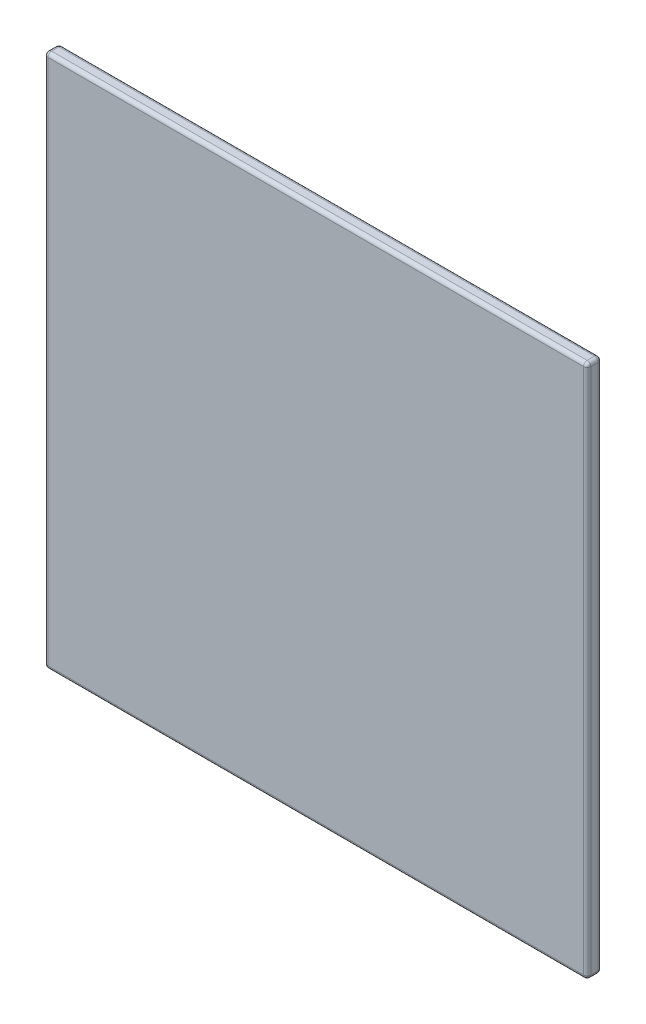
SolidWorks part; units mm, degrees
ref_plane "Front Plane" through (0, 0, 0) normal (0, 0, 1) x (1, 0, 0)
ref_plane "Top Plane" through (0, 0, 0) normal (0, 1, 0) x (1, 0, 0)
ref_plane "Right Plane" through (0, 0, 0) normal (1, 0, 0) x (0, 0, -1)
sketch "Sketch1" plane through (0, 0, 0) normal (0, 0, 1) x (1, 0, 0)
  line L1 (-37.35, -36.75) -> (37.35, -36.75)
  line L2 (-37.35, -36.75) -> (-37.35, 36.75)
  line L3 (-37.35, 36.75) -> (37.35, 36.75)
  line L4 (37.35, -36.75) -> (37.35, 36.75)
  line L5 (-37.35, -36.75) -> (37.35, 36.75) construction
  line L6 (-37.35, 36.75) -> (37.35, -36.75) construction
  point P0 (0, 0)
  dimension "D1" = 74.7
  dimension "D2" = 73.5
extrude "Boss-Extrude1" add sketch "Sketch1" along normal blind 2
fillet "Fillet1" radius 0.5 12 edges at (0, -36.75, 2) (0, -36.75, 0) (-37.35, 0, 2) (-37.35, -36.75, 1) (-37.35, 0, 0) (0, 36.75, 2) (-37.35, 36.75, 1) (0, 36.75, 0) (37.35, -36.75, 1) (37.35, 0, 2) (37.35, 36.75, 1) (37.35, 0, 0)
